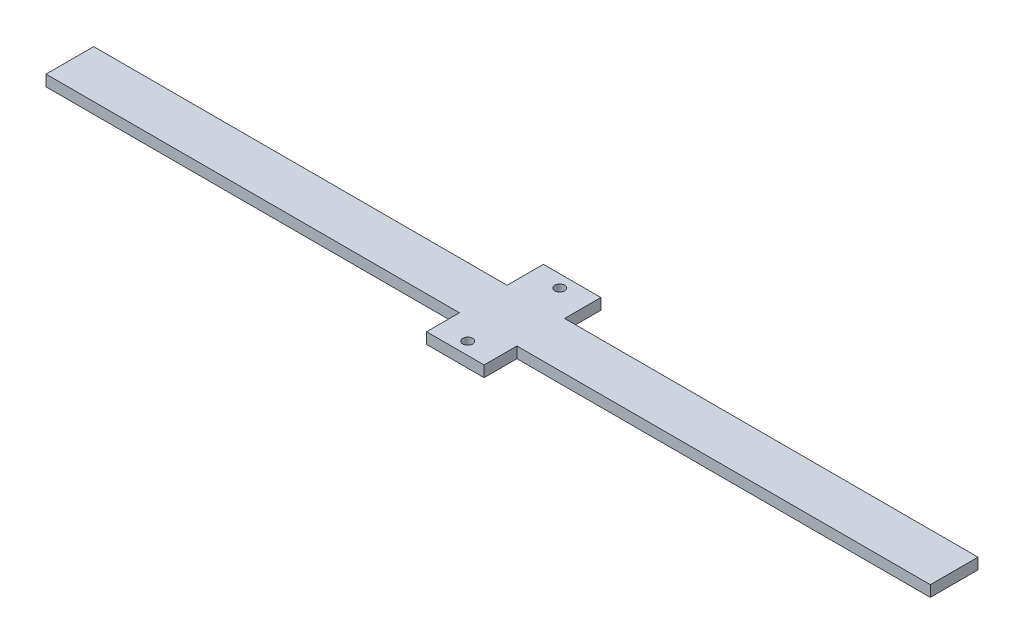
SolidWorks part; units mm, degrees
ref_plane "Front Plane" through (0, 0, 0) normal (0, 0, 1) x (1, 0, 0)
ref_plane "Top Plane" through (0, 0, 0) normal (0, 1, 0) x (1, 0, 0)
ref_plane "Right Plane" through (0, 0, 0) normal (1, 0, 0) x (0, 0, -1)
sketch "Sketch1" plane through (0, 0, 0) normal (0, 1, 0) x (1, 0, 0)
  line L0 (0, 0) -> (0, 13.6906)
  line L1 (0, 13.6906) -> (118.745, 13.6906)
  line L4 (254, 13.6906) -> (254, 0)
  line L5 (254, 0) -> (135.255, 0)
  line L7 (118.745, 13.6906) -> (118.745, 24.1185)
  line L8 (118.745, 24.1185) -> (135.255, 24.1185)
  line L9 (135.255, 24.1185) -> (135.255, 13.6906)
  line L11 (118.745, 0) -> (118.745, -9.4277)
  line L12 (118.745, -9.4277) -> (135.255, -9.4277)
  line L13 (135.255, -9.4277) -> (135.255, 0)
  line L14 (135.255, 13.6906) -> (254, 13.6906)
  line L15 (118.745, 0) -> (0, 0)
  circle A0 centre (127, 20.5625) radius 1.4224
  circle A1 centre (127, -5.8717) radius 1.4224
  point P8 (127, 20.0406)
  point P13 (127, 0)
  dimension "D5" = 2.8448
  dimension "D7" = 2.8448
  dimension "D1" = 13.6906
  dimension "D2" = 254
  dimension "D3" = 16.51
  dimension "D4" = 3.556
  dimension "D6" = 3.556
extrude "Boss-Extrude1" add sketch "Sketch1" along normal blind 3.175
